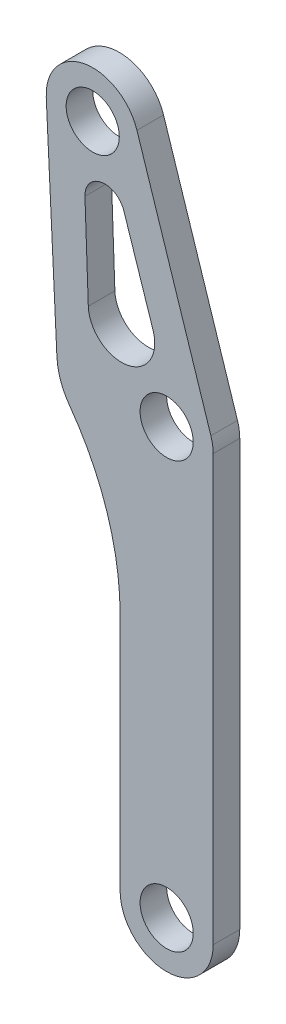
SolidWorks part; units mm, degrees
ref_plane "前视基准面" through (0, 0, 0) normal (0, 0, 1) x (1, 0, 0)
ref_plane "上视基准面" through (0, 0, 0) normal (0, 1, 0) x (1, 0, 0)
ref_plane "右视基准面" through (0, 0, 0) normal (1, 0, 0) x (0, 0, -1)
sketch "草图1" plane through (0, 0, 0) normal (0, 0, 1) x (1, 0, 0)
  line L0 (0, -11.9538) -> (0, 35.5) construction
  line L1 (61.9135, 0) -> (-90.2482, 0) construction
  line L2 (3.5, 32) -> (3.5, 0)
  line L3 (4.0465, 19.5462) -> (-7.8746, 56.2354) construction
  line L4 (-9.0582, 48.9492) -> (-8.1791, 30.8558)
  line L5 (-3.5, 0) -> (-3.5, 18)
  line L6 (-63.1856, -15.3001) -> (29.6687, 62.6138) construction
  line L7 (-2.2336, 50.2006) -> (3.3287, 33.0816)
  line L8 (4.2429, -5.7376) -> (-8.1083, 63.3629) construction
  line L9 (-6.1464, 43.9463) -> (-5.8945, 36.9106)
  line L10 (-3.2225, 44.469) -> (-1.0214, 37.7816)
  arc A0 (-3.5, 0) -> (3.5, 0) centre (0, 0) ccw
  arc A1 (3.5, 32) -> (3.3287, 33.0816) centre (0, 32) ccw
  circle A2 centre (0, 32) radius 2
  circle A3 centre (0, 0) radius 2
  arc A4 (-2.2336, 50.2006) -> (-9.0582, 48.9492) centre (-5.5623, 49.119) ccw
  circle A5 centre (-5.5623, 49.119) radius 2
  arc A6 (-3.5, 18) -> (-8.1791, 30.8558) centre (-23.5, 18) ccw
  arc A7 (-3.2225, 44.469) -> (-6.1464, 43.9463) centre (-4.6473, 44) ccw
  arc A8 (-5.8945, 36.9106) -> (-1.0214, 37.7816) centre (-3.3961, 37) ccw
  point P14 (0, 18)
  dimension "D1" = 7
  dimension "D2" = 4
  dimension "D3" = 4
  dimension "D4" = 3.5
  dimension "D5" = 32
  dimension "D10" = 20
  dimension "D11" = 7
  dimension "D12" = 4
  dimension "D14" = 3
  dimension "D15" = 5
  dimension "D6" = 18
  dimension "D7" = 18
  dimension "D8" = 40
  dimension "D9" = 23.5
  dimension "D13" = 18
  dimension "D16" = 37
  dimension "D17" = 7
  dimension "D18" = 18
extrude "凸台-拉伸2" add sketch "草图1" along normal blind 2
fillet "圆角1" radius 5 1 edges at (-8.1791, 30.8558, 1)
